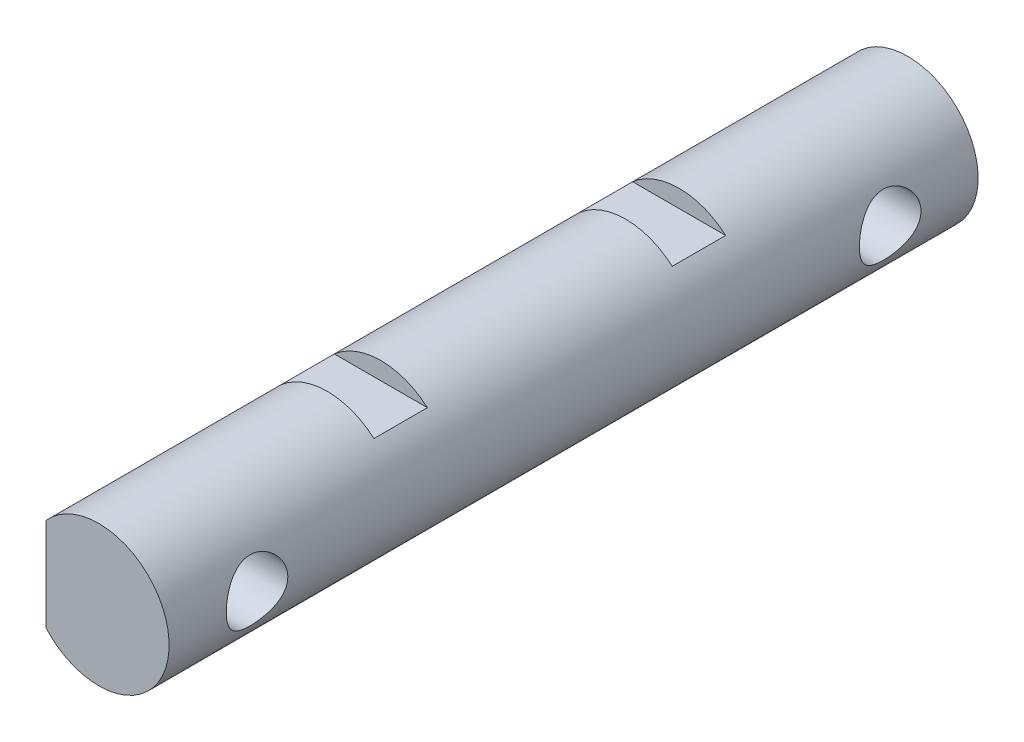
SolidWorks part; units mm, degrees
ref_plane "前视基准面" through (0, 0, 0) normal (0, 0, 1) x (1, 0, 0)
ref_plane "上视基准面" through (0, 0, 0) normal (0, 1, 0) x (1, 0, 0)
ref_plane "右视基准面" through (0, 0, 0) normal (1, 0, 0) x (0, 0, -1)
sketch "草图1" plane through (0, 0, 0) normal (0, 0, 1) x (1, 0, 0)
  line L0 (-87.1056, 0) -> (87.1056, 0) construction
  line L1 (0, 87.1056) -> (0, -87.1056) construction
  circle A0 centre (0, 0) radius 20
  dimension "D1" = 40
extrude "凸台-拉伸1" add sketch "草图1" along normal mid plane 230
sketch "草图2" plane through (0, 0, 115) normal (0, 0, 1) x (1, 0, 0)
  line L1 (40.2653, -15) -> (-40.2653, -15)
  line L2 (40.2653, -15) -> (40.2653, 15)
  line L3 (40.2653, 15) -> (-40.2653, 15)
  line L4 (-40.2653, -15) -> (-40.2653, 15)
  line L5 (40.2653, -15) -> (-40.2653, 15) construction
  line L6 (40.2653, 15) -> (-40.2653, -15) construction
  point P0 (0, 0)
  dimension "D1" = 30
extrude "切除-拉伸1" cut sketch "草图2" against normal blind 15.2 from offset 65 flip side to cut offset against normal yes
sketch "草图3" plane through (0, 0, 115) normal (0, 0, 1) x (1, 0, 0)
  line L0 (-15, -13.2288) -> (-15, 13.2288)
  circle A0 centre (0, 0) radius 20 construction
  circle A1 centre (0, 0) radius 20
  circle M1 centre (0, 0) radius 20
  dimension "D1" = 15
extrude "切除-拉伸2" cut sketch "草图3" against normal blind 50 contours L0 M1
hole_wizard "M20 螺纹孔1" positions "草图5" profile "草图4" tap size "M20" standard "GB"
sketch "草图5" plane through (-15, 0, 0) normal (-1, 0, 0) x (0, -1, 0)
  line L0 (0, 65) -> (0, 115) construction
  line L1 (13.2288, 65) -> (-13.2288, 65) construction
  line L2 (13.2288, 115) -> (-13.2288, 115) construction
  point P0 (0, 90)
  dimension "D1" = 25
sketch "草图4" plane through (-15, 0, 90) normal (0, 1, 0) x (0, 0, 1)
  line L0 (0, 0) -> (0, 52.7575)
  line L1 (0, 52.7575) -> (8.75, 47.5)
  line L2 (8.75, 47.5) -> (8.75, 0)
  line L5 (8.75, 0) -> (0, 0)
  line L10 (0, 52.7575) -> (-8.75, 47.5) construction
  line L11 (0, -6.35) -> (0, 107.95) construction
  dimension "螺纹孔钻头直径" = 17.5
  dimension "螺纹孔钻头深度" = 47.5
  dimension "导头角度" = 118
cosmetic thread "孔螺蚊线1" parameters "D1"=35, "D2"=20
mirror "镜向1" about plane through (0, 0, 0) normal (0, 0, 1) of "M20 螺纹孔1", "切除-拉伸2", "切除-拉伸1"
